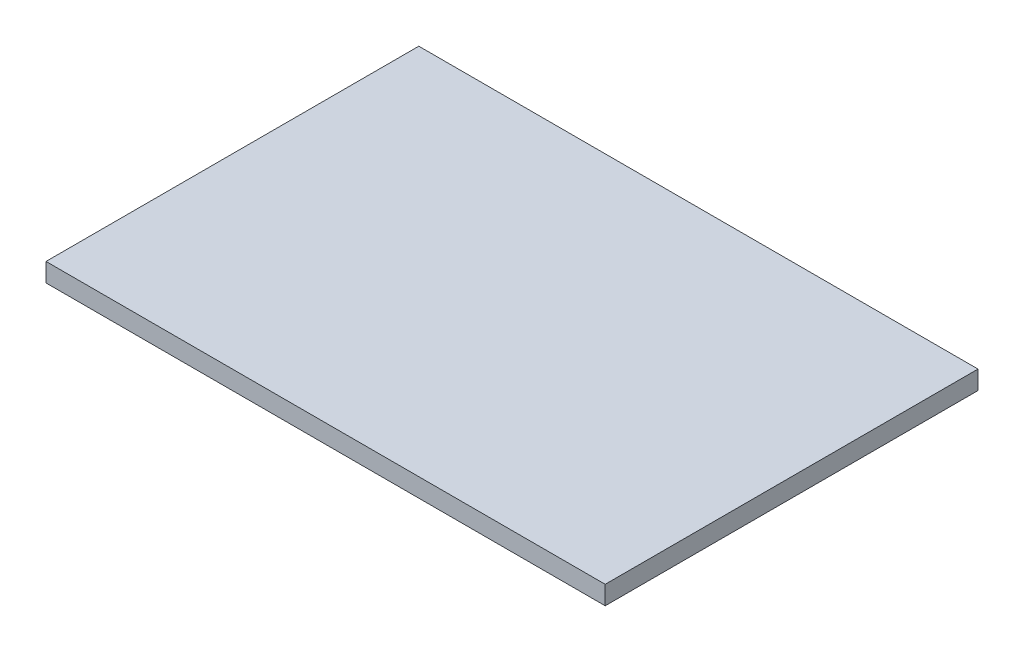
SolidWorks part; units mm, degrees
ref_plane "Front Plane" through (0, 0, 0) normal (0, 0, 1) x (1, 0, 0)
ref_plane "Top Plane" through (0, 0, 0) normal (0, 1, 0) x (1, 0, 0)
ref_plane "Right Plane" through (0, 0, 0) normal (1, 0, 0) x (0, 0, -1)
sketch "Sketch1" plane through (0, 0, 0) normal (0, 1, 0) x (1, 0, 0)
  line L1 (0, 0) -> (90, 0)
  line L2 (0, 0) -> (0, 60)
  line L3 (0, 60) -> (90, 60)
  line L4 (90, 0) -> (90, 60)
  dimension "D1" = 90
  dimension "D2" = 60
extrude "Boss-Extrude1" add sketch "Sketch1" along normal blind 3
